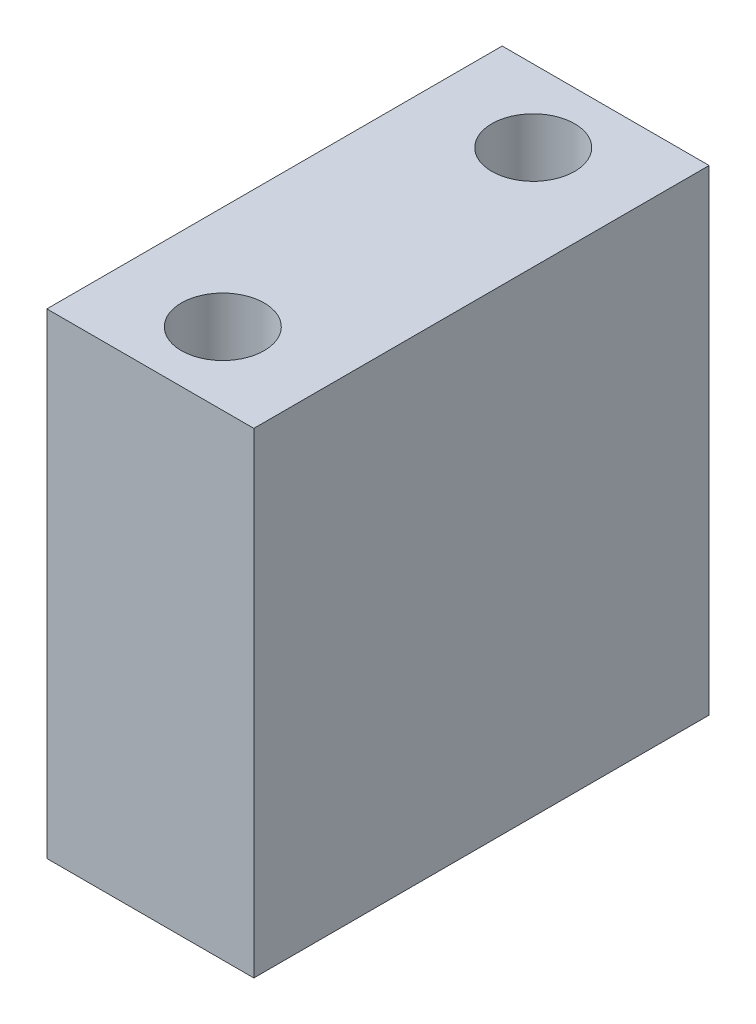
SolidWorks part; units mm, degrees
ref_plane "Front Plane" through (0, 0, 0) normal (0, 0, 1) x (1, 0, 0)
ref_plane "Top Plane" through (0, 0, 0) normal (0, 1, 0) x (1, 0, 0)
ref_plane "Right Plane" through (0, 0, 0) normal (1, 0, 0) x (0, 0, -1)
sketch "Sketch1" plane through (0, 0, 0) normal (0, 1, 0) x (1, 0, 0)
  line L0 (0, -55) -> (0, 55) construction
  line L1 (-5, 11) -> (5, 11)
  line L2 (-5, 11) -> (-5, -11)
  line L3 (-5, -11) -> (5, -11)
  line L4 (5, 11) -> (5, -11)
  line L5 (-5, 11) -> (5, -11) construction
  line L6 (-5, -11) -> (5, 11) construction
  line L7 (-55, 0) -> (55, 0) construction
  circle A0 centre (0, 7.5) radius 2
  circle A1 centre (0, -7.5) radius 2
  point P0 (0, 0)
  dimension "D3" = 4
  dimension "D4" = 4
  dimension "D1" = 10
  dimension "D2" = 22
  dimension "D5" = 7.5
  dimension "D6" = 7.5
extrude "Boss-Extrude1" add sketch "Sketch1" along normal blind 23
equation "\"D4@Sketch1\"=\"D3@Sketch1\""
equation "\"D6@Sketch1\"=\"D5@Sketch1\""
